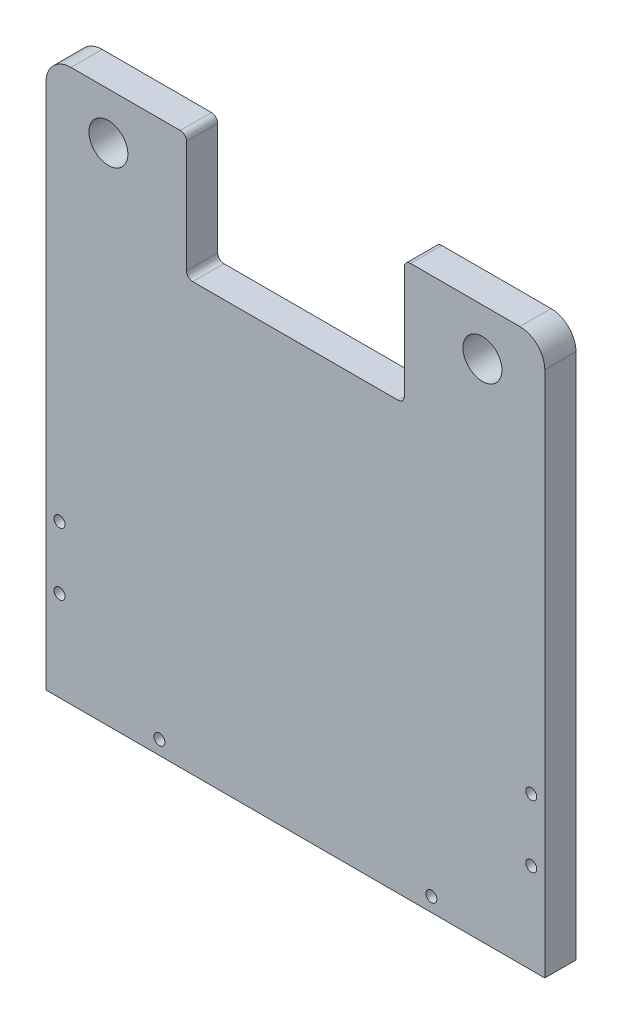
SolidWorks part; units mm, degrees
ref_plane "Front Plane" through (0, 0, 0) normal (0, 0, 1) x (1, 0, 0)
ref_plane "Top Plane" through (0, 0, 0) normal (0, 1, 0) x (1, 0, 0)
ref_plane "Right Plane" through (0, 0, 0) normal (1, 0, 0) x (0, 0, -1)
sketch "Sketch1" plane through (0, 0, 0) normal (0, 0, 1) x (1, 0, 0)
  line L0 (40.0625, 177) -> (43.0625, 177)
  line L1 (0, 0) -> (40, 0)
  line L2 (0, 0) -> (0, 169)
  line L3 (8, 177) -> (40, 177)
  line L5 (20, 177) -> (20, 162) construction
  line L6 (40, 177) -> (40.0625, 177)
  line L7 (40, 162) -> (0, 162) construction
  line L8 (160, 0) -> (120, 0)
  line L13 (160, 0) -> (160, 169)
  line L15 (152, 177) -> (120, 177)
  line L16 (40, 0) -> (120, 0)
  line L17 (116.9375, 177) -> (120, 177)
  line L18 (45.0625, 175) -> (45.0625, 139)
  line L19 (47.0625, 137) -> (112.9375, 137)
  line L20 (80, 137) -> (80, 175) construction
  line L21 (114.9375, 175) -> (114.9375, 139)
  arc A0 (0, 169) -> (8, 177) centre (8, 169) cw
  circle A2 centre (20, 162) radius 6.25
  circle A4 centre (140, 162) radius 6.25
  arc A5 (160, 169) -> (152, 177) centre (152, 169) ccw
  circle A6 centre (4.3284, 49) radius 1.75
  circle A7 centre (4.3284, 29) radius 1.75
  circle A10 centre (36.3713, 4.5) radius 1.75
  circle A12 centre (123.6287, 4.5) radius 1.75
  circle A13 centre (155.6716, 29) radius 1.75
  circle A14 centre (155.6716, 49) radius 1.75
  arc A18 (43.0625, 177) -> (45.0625, 175) centre (43.0625, 175) cw
  arc A19 (114.9375, 175) -> (116.9375, 177) centre (116.9375, 175) cw
  arc A20 (112.9375, 137) -> (114.9375, 139) centre (112.9375, 139) ccw
  arc A21 (47.0625, 137) -> (45.0625, 139) centre (47.0625, 139) cw
  point P7 (0, 177)
  point P40 (117.081, 177)
  dimension "D3" = 8
  dimension "D4" = 12.5
  dimension "D5" = 120
  dimension "D8" = 2
  dimension "D1" = 160
  dimension "D2" = 177
extrude "Boss-Extrude1" add sketch "Sketch1" along normal blind 10
